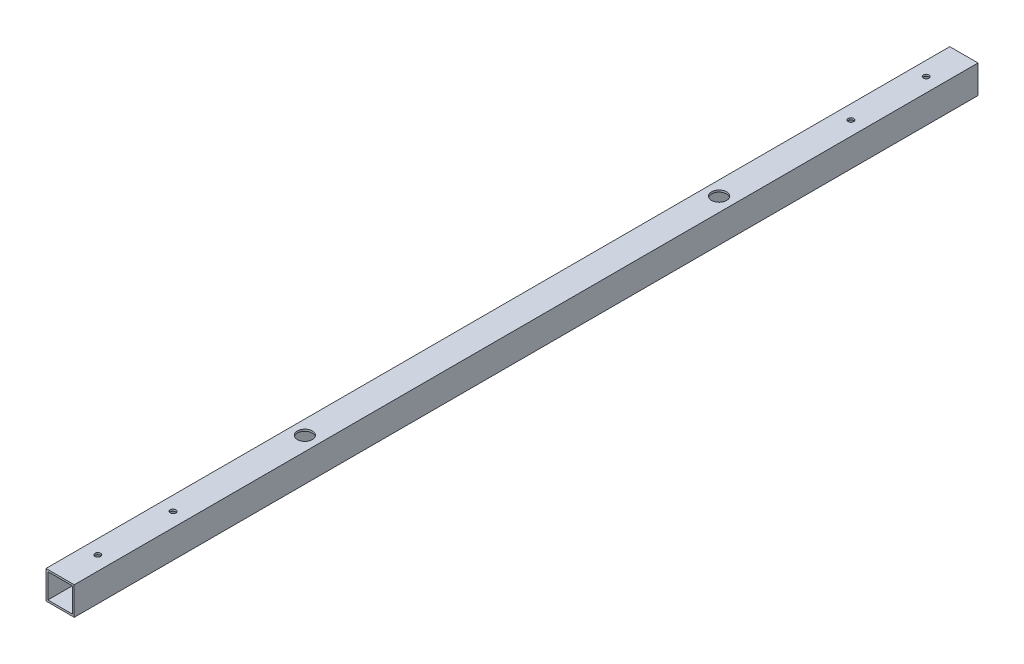
SolidWorks part; units mm, degrees
ref_plane "前视基准面" through (0, 0, 0) normal (0, 0, 1) x (1, 0, 0)
ref_plane "上视基准面" through (0, 0, 0) normal (0, 1, 0) x (1, 0, 0)
ref_plane "右视基准面" through (0, 0, 0) normal (1, 0, 0) x (0, 0, -1)
sketch "草图1" plane through (0, 0, 0) normal (0, 0, 1) x (1, 0, 0)
  line L0 (-6.5, 6.5) -> (6.5, 6.5)
  line L1 (-7.5, -7.5) -> (7.5, -7.5)
  line L2 (-7.5, -7.5) -> (-7.5, 7.5)
  line L3 (-7.5, 7.5) -> (7.5, 7.5)
  line L4 (7.5, -7.5) -> (7.5, 7.5)
  line L5 (-7.5, -7.5) -> (7.5, 7.5) construction
  line L6 (-7.5, 7.5) -> (7.5, -7.5) construction
  line L7 (6.5, -6.5) -> (6.5, 6.5)
  line L8 (-6.5, -6.5) -> (6.5, -6.5)
  line L9 (-6.5, -6.5) -> (-6.5, 6.5)
  point P0 (0, 0)
  dimension "D1" = 15
  dimension "D2" = 15
  dimension "D3" = 1
extrude "凸台-拉伸1" add sketch "草图1" along normal blind 460
sketch "草图2" plane through (0, 7.5, 0) normal (0, 1, 0) x (1, 0, 0)
  line L0 (7.5, 0) -> (-7.5, 0) construction
  line L1 (-67.095, -230) -> (148.9545, -230) construction
  circle A0 centre (0, -120) radius 1.5
  circle A1 centre (0, -340) radius 1.5
  dimension "D1" = 120
extrude "切除-拉伸1" cut sketch "草图2" against normal blind 480
sketch "草图3" plane through (0, 7.5, 0) normal (0, 1, 0) x (1, 0, 0)
  circle A0 centre (0, -120) radius 4
  circle A1 centre (0, -340) radius 4
extrude "切除-拉伸2" cut sketch "草图3" against normal blind 2
sketch "草图4" plane through (0, 0, 0) normal (0, 0, -1) x (-1, 0, 0)
  line L4 (-7.5, 7.5) -> (-7.5, -7.5)
  line L5 (-7.5, -7.5) -> (7.5, -7.5)
  line L6 (7.5, -7.5) -> (7.5, 7.5)
  line L7 (7.5, 7.5) -> (-7.5, 7.5)
  line L8 (-7.5, 7.5) -> (-7.5, -7.5)
  line L9 (-7.5, -7.5) -> (7.5, -7.5)
  line L10 (7.5, -7.5) -> (7.5, 7.5)
  line L11 (7.5, 7.5) -> (-7.5, 7.5)
  dimension "D1" = 0
extrude "凸台-拉伸2" add sketch "草图4" along normal blind 10
sketch "草图5" plane through (0, 0, 460) normal (0, 0, 1) x (1, 0, 0)
  line L4 (7.5, -7.5) -> (7.5, 7.5)
  line L5 (7.5, 7.5) -> (-7.5, 7.5)
  line L6 (-7.5, 7.5) -> (-7.5, -7.5)
  line L7 (-7.5, -7.5) -> (7.5, -7.5)
  line L8 (7.5, -7.5) -> (7.5, 7.5)
  line L9 (7.5, 7.5) -> (-7.5, 7.5)
  line L10 (-7.5, 7.5) -> (-7.5, -7.5)
  line L11 (-7.5, -7.5) -> (7.5, -7.5)
  dimension "D1" = 0
extrude "凸台-拉伸3" add sketch "草图5" along normal blind 10
sketch "草图6" plane through (0, 0, 470) normal (0, 0, 1) x (1, 0, 0)
  line L0 (-7.5, 7.5) -> (-7.5, -7.5) construction
  line L1 (6.5, -6.5) -> (-6.5, -6.5)
  line L2 (6.5, -6.5) -> (6.5, 6.5)
  line L3 (6.5, 6.5) -> (-6.5, 6.5)
  line L4 (-6.5, -6.5) -> (-6.5, 6.5)
  line L5 (6.5, -6.5) -> (-6.5, 6.5) construction
  line L6 (6.5, 6.5) -> (-6.5, -6.5) construction
  line L7 (-7.5, -7.5) -> (7.5, -7.5) construction
  point P0 (0, 0)
  dimension "D1" = 1
  dimension "D2" = 1
extrude "切除-拉伸3" cut sketch "草图6" against normal through all
sketch "草图7" plane through (0, -7.5, 0) normal (0, -1, 0) x (1, 0, 0)
  line L0 (7.5, -10) -> (-7.5, -10) construction
  line L1 (-54.5526, 230) -> (66.5218, 230) construction
  circle A0 centre (0, 10) radius 1.5
  circle A1 centre (0, 50) radius 1.5
  circle A2 centre (0, 450) radius 1.5
  circle A3 centre (0, 410) radius 1.5
  dimension "D1" = 20
  dimension "D2" = 40
extrude "切除-拉伸4" cut sketch "草图7" against normal through all
